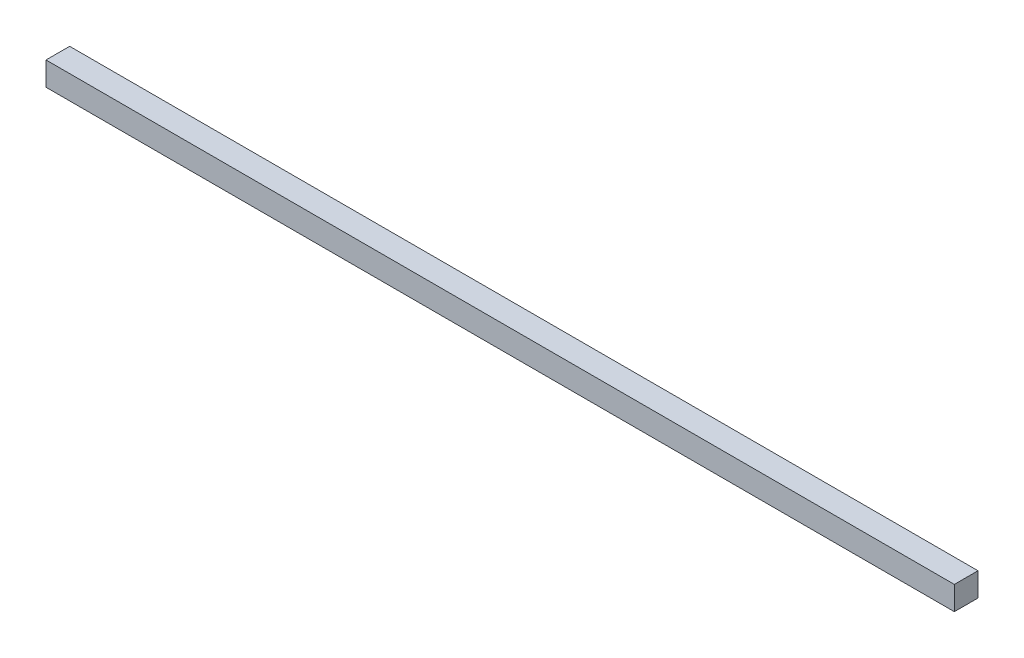
SolidWorks part; units mm, degrees
material "Plain Carbon Steel"
ref_plane "Front Plane" through (0, 0, 0) normal (0, 0, 1) x (1, 0, 0)
ref_plane "Top Plane" through (0, 0, 0) normal (0, 1, 0) x (1, 0, 0)
ref_plane "Right Plane" through (0, 0, 0) normal (1, 0, 0) x (0, 0, -1)
sketch "Sketch1" plane through (0, 0, 0) normal (0, 0, 1) x (1, 0, 0)
  line L0 (-192, -5) -> (192, -5)
  line L1 (192, -5) -> (192, 5)
  line L2 (192, 5) -> (-192, 5)
  line L3 (-192, 5) -> (-192, -5)
  dimension "D1" = 384
  dimension "D2" = 10
  dimension "D3" = 192
  dimension "D4" = 5
extrude "Boss-Extrude1" add sketch "Sketch1" along normal mid plane 10
